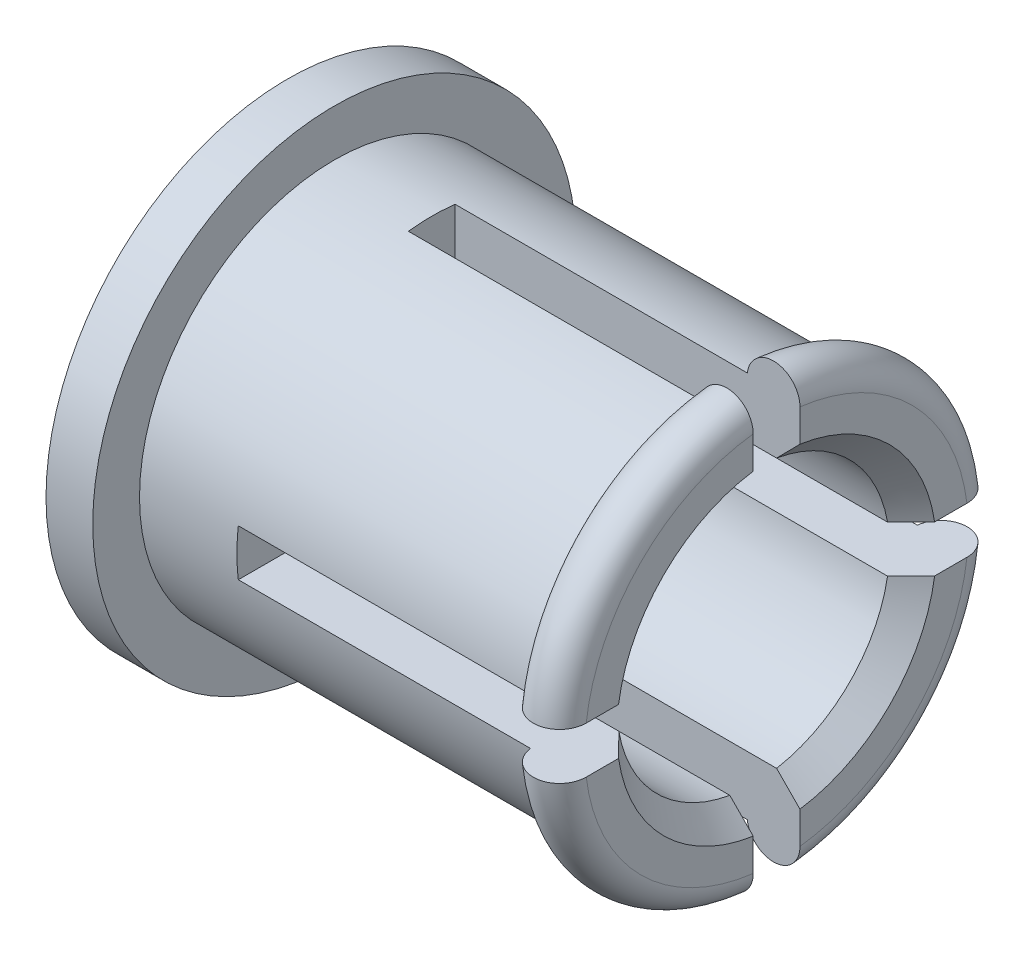
SolidWorks part; units mm, degrees
material "PET"
ref_plane "Front Plane" through (0, 0, 0) normal (0, 0, 1) x (1, 0, 0)
ref_plane "Top Plane" through (0, 0, 0) normal (0, 1, 0) x (1, 0, 0)
ref_plane "Right Plane" through (0, 0, 0) normal (1, 0, 0) x (0, 0, -1)
sketch "Sketch1" plane through (0, 0, 0) normal (0, 0, 1) x (1, 0, 0)
  line L1 (0, 0) -> (15.9396, 0)
  line L3 (1.524, 6.35) -> (14.224, 6.35)
  line L7 (0, 7.874) -> (1.524, 7.874)
  line L8 (1.524, 6.35) -> (1.524, 7.874)
  line L11 (0, 7.874) -> (0, 0)
  line L12 (15.9396, 6.2514) -> (15.9396, 0)
  line L13 (0, 0) -> (-4.6555, 0) construction
  arc A0 (15.9396, 6.2514) -> (14.224, 6.35) centre (15.079, 6.2514) ccw
  point P2 (15.875, 6.3868)
  point P10 (18.0057, 6.0811)
  dimension "D4" = 0.8606
  dimension "D1" = 12.7
  dimension "D2" = 1.524
  dimension "D3" = 1.524
  dimension "D5" = 0.762
  dimension "D6" = 12.7
revolve "Revolve1" add sketch "Sketch1" angle 360 about L1
sketch "Sketch2" plane through (0, 0, 0) normal (-1, 0, 0) x (0, 0, 1)
  circle A0 centre (0, 0) radius 4.445
  dimension "D1" = 8.89
extrude "Cut-Extrude1" cut sketch "Sketch2" against normal blind 18.034
chamfer "Chamfer1" distance 0.762 angle 45 2 edges at (15.9396, 0, 4.445) (0, 0, 4.445)
sketch "Sketch5" plane through (0, 0, 0) normal (0, 0, 1) x (1, 0, 0)
  line L0 (15.9396, -6.2514) -> (15.9396, 6.2514) construction
  line L1 (15.9396, 0.762) -> (4.699, 0.762)
  line L2 (15.9396, 0.762) -> (15.9396, -0.762)
  line L3 (15.9396, -0.762) -> (4.699, -0.762)
  line L4 (4.699, 0.762) -> (4.699, -0.762)
  line L5 (1.524, -6.35) -> (1.524, 6.35) construction
  line L7 (0, 0) -> (4.699, 0) construction
  point P4 (0, 0)
  point P5 (15.9396, 0.5421)
  point P10 (0, 0)
  dimension "D1" = 1.524
  dimension "D2" = 3.175
extrude "Cut-Extrude2" cut sketch "Sketch5" against normal through all
pattern_circular "CirPattern1" count 4 over 360 about axis through (0, 0, 0) along (1, 0, 0) of "Cut-Extrude2"
